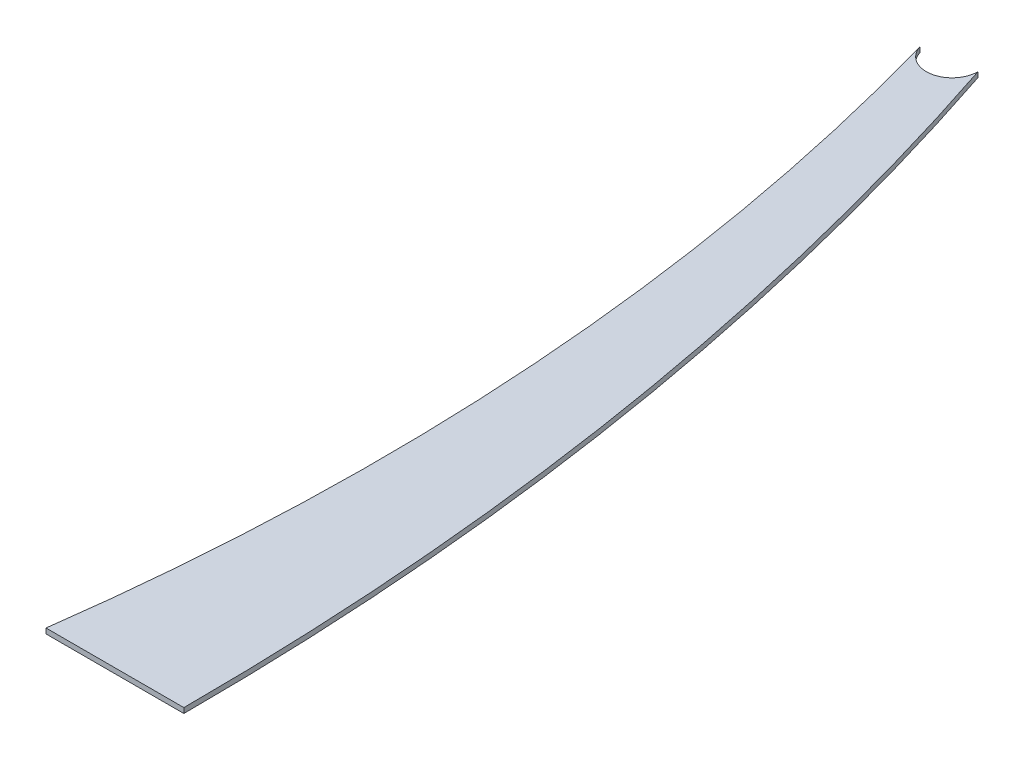
SolidWorks part; units mm, degrees
ref_plane "Спереди" through (0, 0, 0) normal (0, 0, 1) x (1, 0, 0)
ref_plane "Сверху" through (0, 0, 0) normal (0, 1, 0) x (1, 0, 0)
ref_plane "Справа" through (0, 0, 0) normal (1, 0, 0) x (0, 0, -1)
sketch "Эскиз1" plane through (0, 0, 0) normal (0, 1, 0) x (1, 0, 0)
  line L0 (-18.3166, 1100) -> (282.2031, 1100) construction
  line L1 (0, 0) -> (160, 0)
  line L2 (-77.1794, 1091.8183) -> (-18.3166, 1100) construction
  arc A0 (-18.3166, 1100) -> (-77.1794, 1091.8183) centre (-48.3166, 1100) cw
  arc A1 (160, 0) -> (-18.3166, 1100) centre (-3322, 0) ccw
  arc A2 (-77.1794, 1091.8183) -> (0, 0) centre (-2655.5864, 360.9167) cw
  point P7 (-71.3385, 1080.7648)
  point P9 (282.2031, 1100)
  dimension "D1" = 30
  dimension "D4" = 3482
  dimension "D5" = 2680
  dimension "D2" = 1100
  dimension "D3" = 160
  dimension "D6" = 59.4287
extrude "Бобышка-Вытянуть1" add sketch "Эскиз1" along normal mid plane 6
